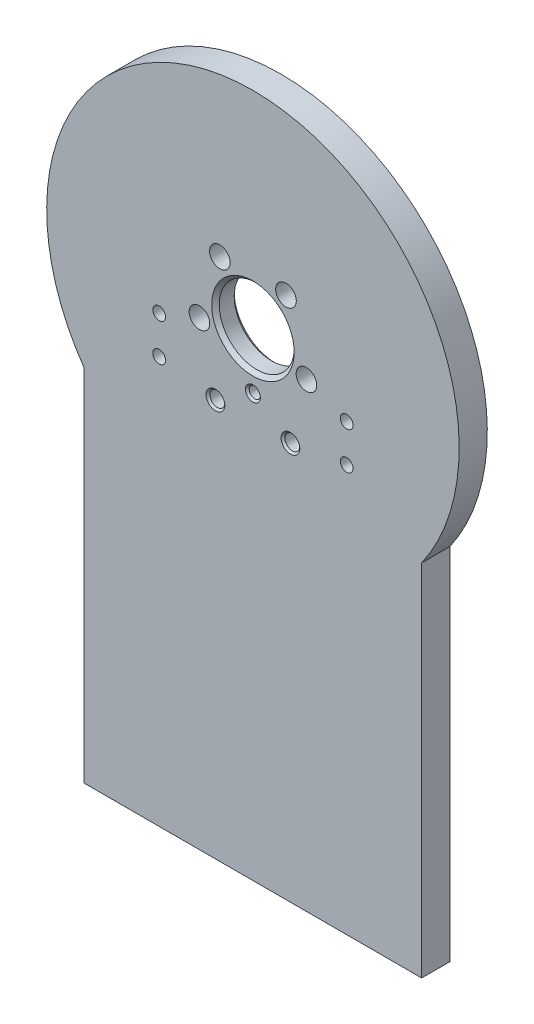
SolidWorks part; units mm, degrees
material "Q235"
ref_plane "前视基准面" through (0, 0, 0) normal (0, 0, 1) x (1, 0, 0)
ref_plane "上视基准面" through (0, 0, 0) normal (0, 1, 0) x (1, 0, 0)
ref_plane "右视基准面" through (0, 0, 0) normal (1, 0, 0) x (0, 0, -1)
ref_plane "基准面1" through (0, 0, 1) normal (0, 0, 1) x (1, 0, 0)
sketch "草图2" plane through (0, 0, 1) normal (0, 0, 1) x (1, 0, 0)
  circle A1 centre (18.5566, -25.5225) radius 150
  dimension "D1" = 300
extrude "凸台-拉伸1" add sketch "草图2" along normal blind 15
sketch "草图3" plane through (0, 0, 1) normal (0, 0, -1) x (-1, 0, 0)
  circle A0 centre (-18.5566, -25.5225) radius 35
  dimension "D1" = 70
extrude "切除-拉伸1" cut sketch "草图3" against normal blind 3
sketch "草图4" plane through (0, 0, 1) normal (0, 0, -1) x (-1, 0, 0)
  circle A0 centre (-18.5566, -25.5225) radius 35 construction
  circle A1 centre (-18.5566, -25.5225) radius 35
  circle A2 centre (-18.5566, -25.5225) radius 38.5
  dimension "D1" = 77
extrude "凸台-拉伸2" add sketch "草图4" along normal up to surface (16.5 mm away)
sketch "草图5" plane through (0, 0, 1) normal (0, 0, -1) x (-1, 0, 0)
  circle A0 centre (-18.5566, -25.5225) radius 38.5 construction
  circle A1 centre (-18.5566, -25.5225) radius 38.5
  circle A2 centre (-18.5566, -25.5225) radius 46.5
  dimension "D1" = 8
extrude "凸台-拉伸3" add sketch "草图5" along normal offset from surface (13.5 mm away) 3
chamfer "倒角1" distance 0.5 angle 45 2 edges at (18.5566, 12.9775, -15.5) (18.5566, 9.4775, -15.5)
hole_wizard "打孔尺寸根据内六角圆柱头螺钉的类型1" positions "草图8" profile "草图7" counterbore size "M6" standard "GB"
sketch "草图8" plane through (42.6264, -13.4634, 16) normal (0, 0, 1) x (1, 0, 0)
  line L0 (-24.0698, -12.0592) -> (-24.0698, 17.9408) construction
  line L2 (-24.0698, -12.0592) -> (-41.7034, 12.2114) construction
  line L3 (-24.0698, -12.0592) -> (-52.6015, -21.3297) construction
  line L6 (-24.0698, -12.0592) -> (4.4619, -21.3297) construction
  line L9 (-6.4362, 12.2114) -> (-24.0698, -12.0592) construction
  circle A0 centre (-24.0698, -12.0592) radius 30 construction
  circle A1 centre (-24.0698, -12.0592) radius 150 construction
  point P0 (-41.7034, 12.2114)
  point P45 (-6.4362, 12.2114)
  point P46 (4.4619, -21.3297)
  point P48 (-52.6015, -21.3297)
  point P50 (-24.0698, -42.0592) [skipped]
  dimension "D1" = 60
  dimension "D2" = 36
  dimension "D4" = 72
  dimension "D5" = 72
  dimension "D3" = 5
sketch "草图7" plane through (0.9231, -1.252, 16) normal (1, 0, 0) x (0, -1, 0)
  line L0 (0, 0) -> (0, 31.5)
  line L1 (0, 31.5) -> (3.3, 31.5)
  line L3 (3.3, 31.5) -> (3.3, 8)
  line L4 (3.3, 8) -> (5.5, 8)
  line L5 (5.5, 8) -> (5.5, 0)
  line L7 (5.5, 0) -> (0, 0)
  line L11 (0, -6.35) -> (0, 107.95) construction
  dimension "通孔孔直径" = 6.6
  dimension "通孔孔深度" = 31.5
  dimension "柱形沉头孔直径" = 11
  dimension "柱形沉头孔深度" = 8
hole_wizard "Ø6.0 (6) 直径孔1" positions "草图10" profile "草图9" hole size "Ø6.0" standard "ISO" end condition through all
sketch "草图10" plane through (0, 0, 16) normal (0, 0, 1) x (1, 0, 0)
  line L0 (-9.9751, -34.793) -> (47.0883, -34.793) construction
  line L2 (18.5566, -25.5225) -> (18.5566, -51.9555) construction
  circle A0 centre (18.5566, -25.5225) radius 30 construction
  circle A1 centre (18.5566, -25.5225) radius 150 construction
  point P0 (18.5566, -55.5225)
sketch "草图9" plane through (18.5566, -55.5225, 16) normal (1, 0, 0) x (0, -1, 0)
  line L0 (0, 0) -> (0, 31.5)
  line L1 (0, 31.5) -> (3, 31.5)
  line L2 (3, 31.5) -> (3, 0)
  line L5 (3, 0) -> (0, 0)
  line L11 (0, -6.35) -> (0, 107.95) construction
  dimension "通孔孔直径" = 6
  dimension "通孔孔深度" = 31.5
chamfer "倒角3" distance 1 angle 45 1 edges at (21.5566, -55.5225, 16)
ref_plane "基准面2" through (0, 0, 11) normal (0, 0, -1) x (-1, 0, 0)
sketch "草图20" plane through (0, 0, 1) normal (0, 0, -1) x (-1, 0, 0)
  circle A0 centre (-18.5566, -25.5225) radius 46.5 construction
  circle A1 centre (-18.5566, -25.5225) radius 46.5
extrude "切除-拉伸5" cut sketch "草图20" along normal blind 69
sketch "草图22" plane through (0, 0, 16) normal (0, 0, 1) x (1, 0, 0)
  line L0 (0.9231, -1.252) -> (36.1902, -1.252) construction
  line L1 (18.5566, -25.5225) -> (50.0448, -25.5225) construction
  line L2 (18.5566, -25.5225) -> (18.5566, 3.016) construction
  line L3 (18.5566, -25.5225) -> (18.5566, -68.5225) construction
  line L4 (38.5566, -68.5225) -> (-1.4434, -68.5225) construction
  circle A0 centre (-1.4434, -68.5225) radius 4
  circle A1 centre (38.5566, -68.5225) radius 4
  circle A2 centre (18.5566, -25.5225) radius 150 construction
  dimension "D1" = 8
  dimension "D2" = 40
  dimension "D4" = 43
extrude "切除-拉伸7" cut sketch "草图22" against normal through all
chamfer "倒角6" distance 1 angle 45 2 edges at (42.5566, -68.5225, 16) (2.5566, -68.5225, 16)
hole_wizard "M8 螺纹孔1" positions "草图24" profile "草图23" tap size "M8" standard "GB" end condition through all
sketch "草图24" plane through (0, 0, 16) normal (0, 0, 1) x (1, 0, 0)
  circle A0 centre (18.5566, -25.5225) radius 150 construction
  point P1 (-31.4434, -43.5225)
  point P3 (-31.4434, -63.5225)
  point P5 (68.5566, -43.5225)
  point P7 (68.5566, -63.5225)
  point P10 (18.5566, -25.5225)
  dimension "D4" = 50
  dimension "D1" = 18
  dimension "D2" = 20
  dimension "D3" = 100
cosmetic thread "孔螺蚊线2" parameters "D2"=8
cosmetic thread "孔螺蚊线3" parameters "D2"=8
cosmetic thread "孔螺蚊线4" parameters "D2"=8
cosmetic thread "孔螺蚊线5" parameters "D2"=8
sketch "草图23" plane through (-31.4434, -43.5225, 16) normal (1, 0, 0) x (0, -1, 0)
  line L0 (0, 0) -> (0, 15)
  line L1 (0, 15) -> (3.4, 15)
  line L2 (3.4, 15) -> (3.4, 0)
  line L5 (3.4, 0) -> (0, 0)
  line L11 (0, -6.35) -> (0, 107.95) construction
  dimension "通孔螺纹孔钻头直径" = 6.8
  dimension "通孔螺纹孔钻头深度" = 15
cosmetic thread "孔螺蚊线6" parameters "D2"=8
sketch "草图27" plane through (0, 0, 1) normal (0, 0, -1) x (-1, 0, 0)
  circle A0 centre (-18.5566, -25.5225) radius 40
  circle A1 centre (-18.5566, -25.5225) radius 35 construction
  circle A2 centre (-18.5566, -25.5225) radius 35
  dimension "D1" = 80
extrude "凸台-拉伸4" add sketch "草图27" along normal blind 5
chamfer "倒角7" distance 0.5 angle 45 1 edges at (-16.4434, -25.5225, -4)
chamfer "倒角8" distance 2 angle 45 2 edges at (168.5566, -25.5225, 16) (168.5566, -25.5225, 1)
sketch "草图25" plane through (0, 0, 16) normal (0, 0, 1) x (1, 0, 0)
  circle A0 centre (18.5566, -25.5225) radius 20
  dimension "D1" = 40
extrude "切除-拉伸8" cut sketch "草图25" against normal through all
chamfer "倒角9" distance 2 angle 45 2 edges at (-1.4434, -25.5225, 4) (38.5566, -25.5225, 16)
fillet "圆角1" radius 1 1 edges at (58.5566, -25.5225, 1)
sketch "草图28" plane through (0, 0, 16) normal (0, 0, 1) x (1, 0, 0)
  circle A0 centre (18.5566, -25.5225) radius 110
  dimension "D1" = 220
extrude "切除-拉伸9" cut sketch "草图28" against normal through all flip side to cut
sketch "草图29" plane through (0, 0, 16) normal (0, 0, 1) x (1, 0, 0)
  line L1 (-71.4434, -82.1836) -> (108.5566, -82.1836)
  line L2 (-71.4434, -82.1836) -> (-71.4434, -280.5225)
  line L3 (-71.4434, -280.5225) -> (108.5566, -280.5225)
  line L4 (108.5566, -82.1836) -> (108.5566, -280.5225)
  circle A0 centre (18.5566, -25.5225) radius 110 construction
  circle A1 centre (18.5566, -25.5225) radius 22 construction
  dimension "D1" = 180
  dimension "D2" = 90
  dimension "D3" = 255
extrude "凸台-拉伸5" add sketch "草图29" against normal up to surface (15 mm away) up to face at (-28.0434, -43.5225, 1)
